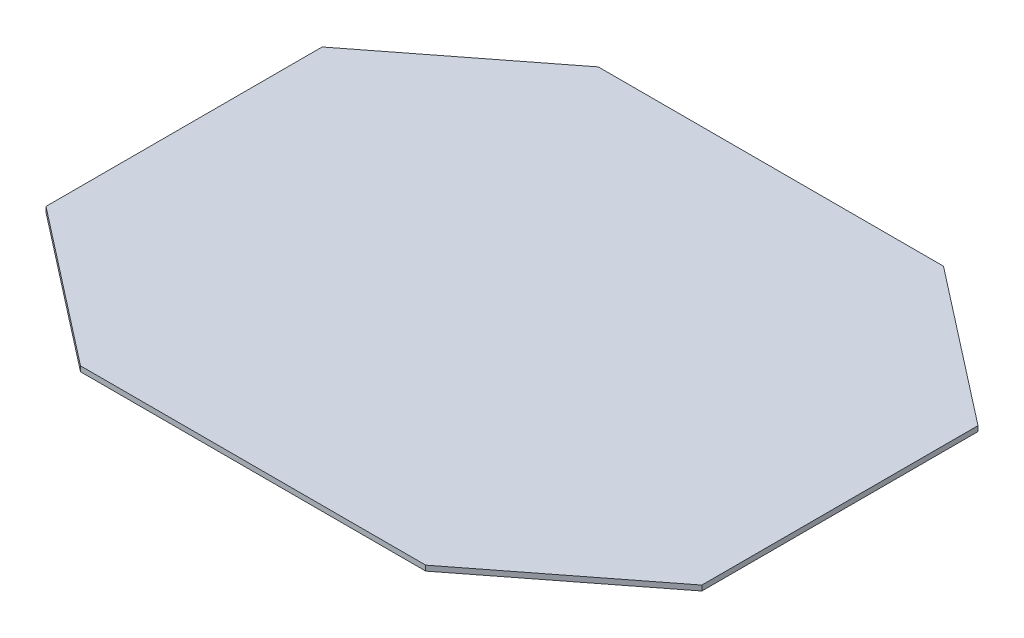
SolidWorks part; units mm, degrees
ref_plane "Front Plane" through (0, 0, 0) normal (0, 0, 1) x (1, 0, 0)
ref_plane "Top Plane" through (0, 0, 0) normal (0, 1, 0) x (1, 0, 0)
ref_plane "Right Plane" through (0, 0, 0) normal (1, 0, 0) x (0, 0, -1)
sketch "Sketch1" plane through (0, 0, 0) normal (0, 1, 0) x (1, 0, 0)
  line L0 (-100, 150) -> (100, 150)
  line L1 (100, 150) -> (190, 80)
  line L2 (190, 80) -> (190, 60)
  line L3 (-190, 60) -> (-190, -60)
  line L4 (190, 60) -> (190, -60)
  line L6 (190, -60) -> (190, -80)
  line L7 (190, -80) -> (100, -150)
  line L8 (100, -150) -> (-100, -150)
  line L9 (-100, -150) -> (-190, -80)
  line L10 (-190, -80) -> (-190, -60)
  line L14 (-190, 60) -> (-190, 80)
  line L15 (-190, 80) -> (-100, 150)
  point P18 (-190, 70)
  point P19 (190, 70)
  point P20 (-190, -70)
  point P21 (190, -70)
  dimension "D1" = 200
  dimension "D2" = 300
  dimension "D3" = 200
  dimension "D5" = 20
  dimension "D6" = 20
  dimension "D8" = 150
  dimension "D10" = 20
  dimension "D12" = 20
  dimension "D15" = 380
  dimension "D16" = 380
  dimension "D19" = 90
extrude "Boss-Extrude1" add sketch "Sketch1" along normal blind 3
